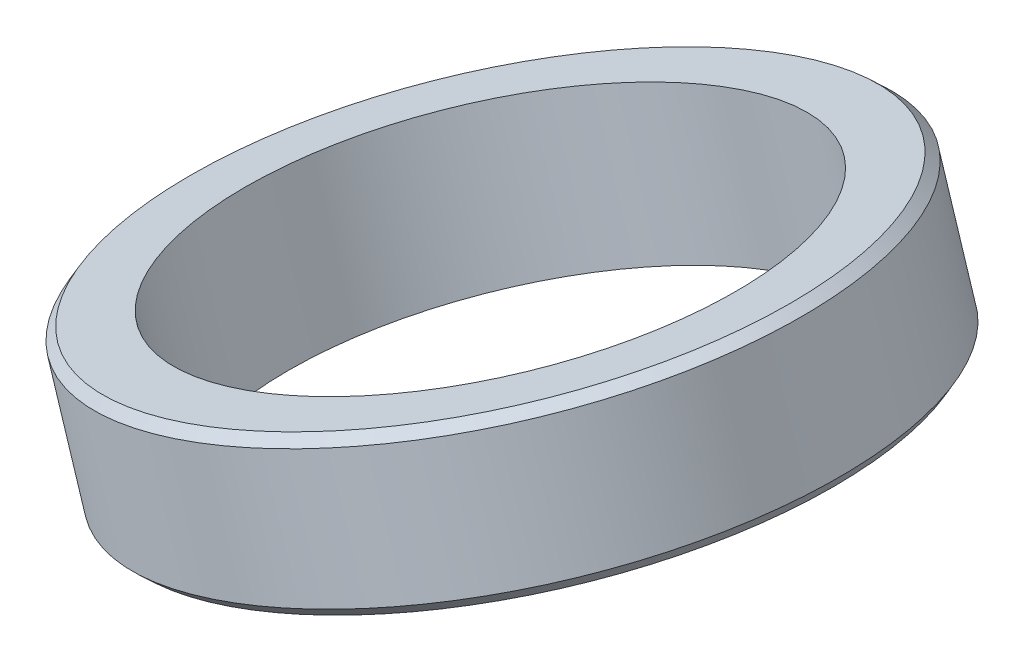
SolidWorks part; units mm, degrees
material "6061-T6 (SS)"
ref_plane "Alzado" through (0, 0, 0) normal (0, 0, 1) x (1, 0, 0)
ref_plane "Planta" through (0, 0, 0) normal (0, 1, 0) x (1, 0, 0)
ref_plane "Vista lateral" through (0, 0, 0) normal (1, 0, 0) x (0, 0, -1)
sketch "Sk_Contratuerca" plane through (0, 0, 0) normal (0, 0, 1) x (1, 0, 0)
  line L0 (370.4131, 564.5802) -> (373.465, 565.5425)
  line L1 (373.465, 565.5425) -> (374.0922, 565.216)
  line L2 (374.0922, 565.216) -> (376.1972, 558.54)
  line L3 (376.1972, 558.54) -> (375.8707, 557.9128)
  line L4 (375.8707, 557.9128) -> (372.8188, 556.9505)
  line L5 (372.8188, 556.9505) -> (370.4131, 564.5802)
  line L6 (355.2714, 565.0486) -> (365.7964, 531.6686) construction
revolve "Contratuerca" add sketch "Sk_Contratuerca" angle 360 about L6
